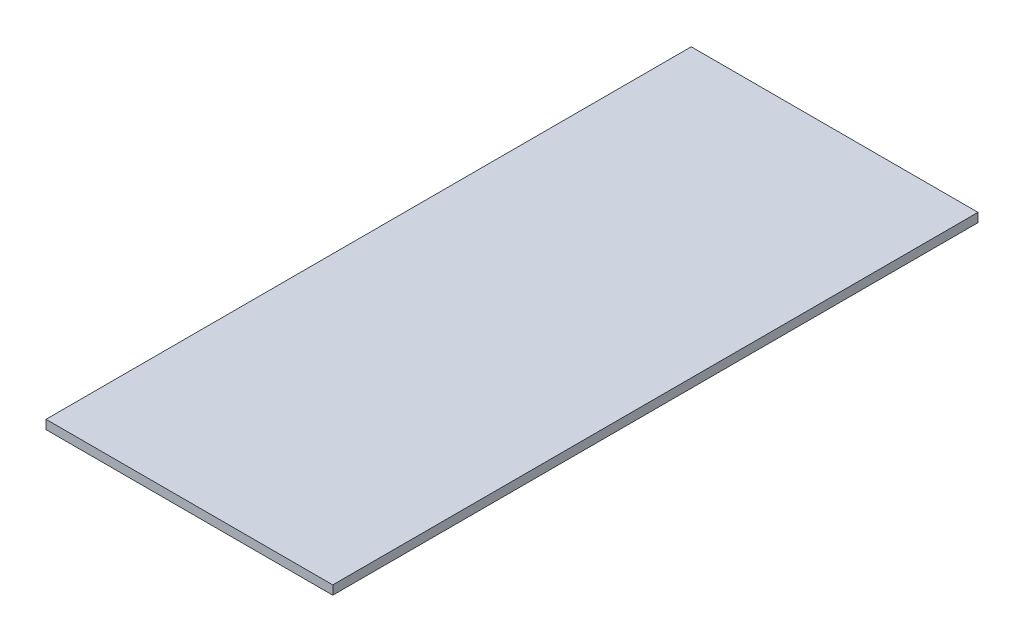
SolidWorks part; units mm, degrees
ref_plane "Front Plane" through (0, 0, 0) normal (0, 0, 1) x (1, 0, 0)
ref_plane "Top Plane" through (0, 0, 0) normal (0, 1, 0) x (1, 0, 0)
ref_plane "Right Plane" through (0, 0, 0) normal (1, 0, 0) x (0, 0, -1)
sketch "Sketch1" plane through (0, 0, 0) normal (0, 1, 0) x (1, 0, 0)
  line L0 (-157.6996, 42.9503) -> (197.9004, 42.9503) construction
  line L1 (-30.6996, 42.9503) -> (70.9004, 42.9503)
  line L2 (-30.6996, 42.9503) -> (-30.6996, -185.6497)
  line L3 (-30.6996, -185.6497) -> (70.9004, -185.6497)
  line L4 (70.9004, 42.9503) -> (70.9004, -185.6497)
  line L5 (-157.6996, -185.6497) -> (197.9004, -185.6497) construction
  point P8 (0, 0)
  point P9 (0, 0)
  dimension "D1" = 127
  dimension "D2" = 127
  dimension "D3" = 101.6
  dimension "D4" = 228.6
extrude "Boss-Extrude1" add sketch "Sketch1" along normal blind 3.175
